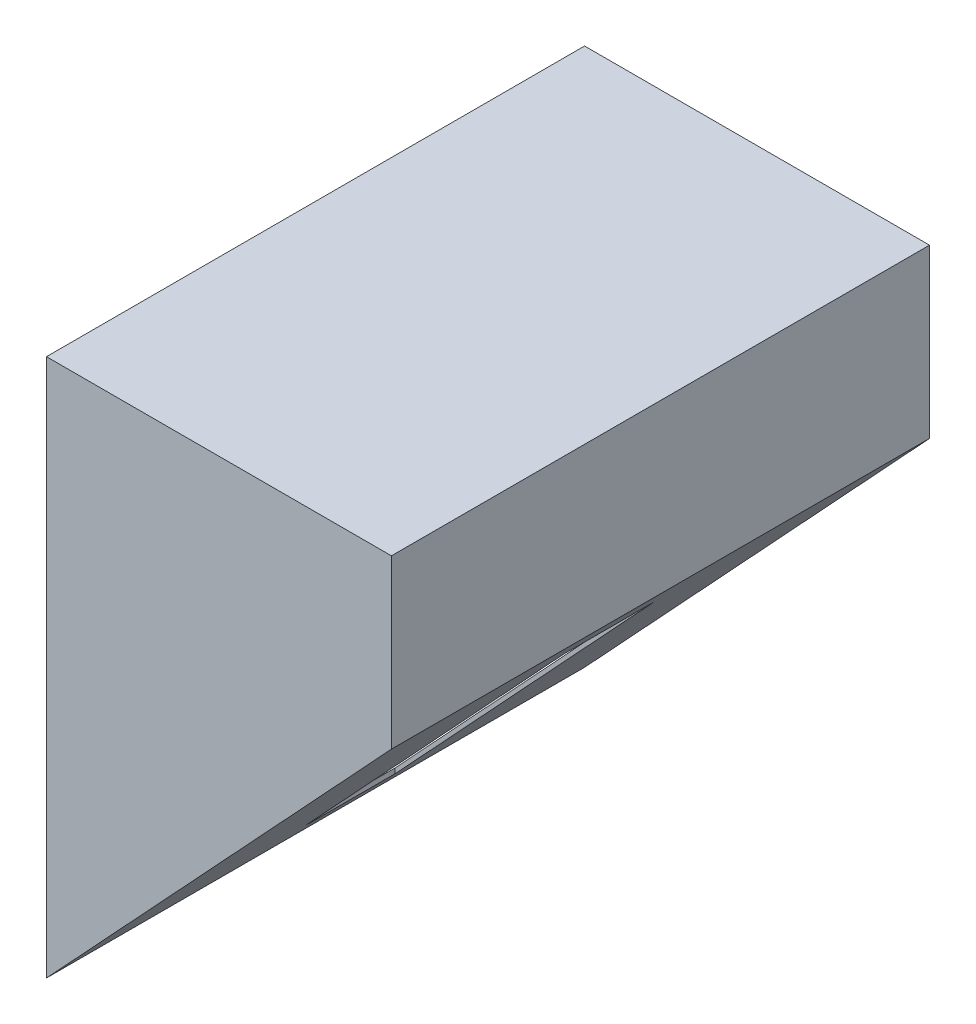
SolidWorks part; units mm, degrees
ref_plane "Plan de face" through (0, 0, 0) normal (0, 0, 1) x (1, 0, 0)
ref_plane "Plan de dessus" through (0, 0, 0) normal (0, 1, 0) x (1, 0, 0)
ref_plane "Plan de droite" through (0, 0, 0) normal (1, 0, 0) x (0, 0, -1)
sketch "Esquisse1" plane through (0, 0, 0) normal (1, 0, 0) x (0, 0, -1)
  line L1 (-81, -112.1701) -> (75, -112.1701)
  line L2 (-81, -112.1701) -> (-81, 43.8299)
  line L3 (-81, 43.8299) -> (75, 43.8299)
  line L4 (75, -112.1701) -> (75, 43.8299)
  point P0 (0, 0)
  dimension "D1" = 156
  dimension "D2" = 156
extrude "Boss.-Extru.3" add sketch "Esquisse1" along normal blind 100
sketch "Esquisse5" plane through (0, -112.1701, 0) normal (0, -1, 0) x (1, 0, 0)
  line L0 (100, 81) -> (0, 81) construction
  line L1 (85, 16) -> (10, 16)
  line L2 (85, 16) -> (85, -10)
  line L3 (85, -10) -> (10, -10)
  line L4 (10, 16) -> (10, -10)
  line L5 (100, -75) -> (0, -75) construction
  line L6 (100, 81) -> (100, -75) construction
  dimension "D1" = 75
  dimension "D2" = 65
  dimension "D3" = 65
  dimension "D4" = 15
extrude "Enlèv. mat.-Extru.4" cut sketch "Esquisse5" against normal blind 100
sketch "Esquisse8" plane through (0, 0, 81) normal (0, 0, 1) x (1, 0, 0)
  line L0 (100, -4.7095) -> (0, -112.1701)
  line L1 (100, 43.8299) -> (100, -112.1701) construction
  line L2 (100, -4.7095) -> (100, -112.1701)
  line L3 (100, -112.1701) -> (0, -112.1701)
extrude "Enlèv. mat.-Extru.11" cut sketch "Esquisse8" against normal through all
shell "Coque6" thickness 1
ref_plane "Plan1" through (9, -11.1701, -11) normal (1, 0, 0) x (0, 0, -1)
sketch "Esquisse10" plane through (0, 0, -11) normal (0, 0, -1) x (-1, 0, 0)
  line L0 (-9, -101.0307) -> (-86, -18.2861)
  line L1 (-86, -18.2861) -> (-86, -11.1701)
  line L2 (-86, -11.1701) -> (-9, -11.1701)
  line L3 (-9, -11.1701) -> (-9, -101.0307)
extrude "Enlèv. mat.-Extru.12" cut sketch "Esquisse10" against normal up to next
